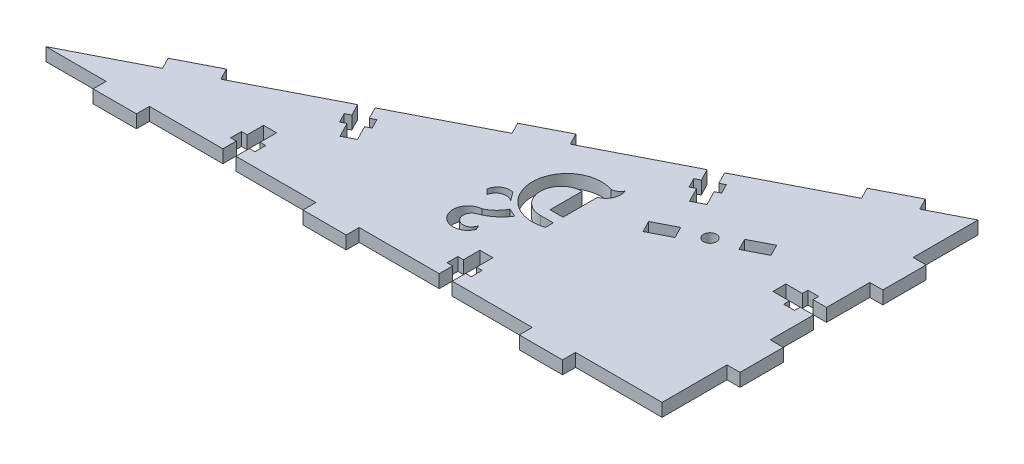
SolidWorks part; units mm, degrees
ref_plane "Front Plane" through (0, 0, 0) normal (0, 0, 1) x (1, 0, 0)
ref_plane "Top Plane" through (0, 0, 0) normal (0, 1, 0) x (1, 0, 0)
ref_plane "Right Plane" through (0, 0, 0) normal (1, 0, 0) x (0, 0, -1)
sketch "Sketch1" plane through (0, 0, 0) normal (0, 1, 0) x (1, 0, 0)
  line L0 (0, 73) -> (-8.8985, 68.4375)
  line L1 (0, 0) -> (-20, 0)
  line L2 (0, 0) -> (0, 15)
  line L5 (-124.5792, 9.125) -> (-125.948, 11.7946)
  line L6 (-125.948, 11.7946) -> (-117.0495, 16.3571)
  line L7 (-117.0495, 16.3571) -> (-115.6807, 13.6875)
  line L8 (-8.8985, 68.4375) -> (-10.2673, 71.1071)
  line L9 (-10.2673, 71.1071) -> (-19.1658, 66.5446)
  line L10 (-19.1658, 66.5446) -> (-17.797, 63.875)
  line L11 (-124.5792, 9.125) -> (-142.3763, 0)
  line L12 (-17.797, 63.875) -> (-38.7085, 53.1531)
  line L13 (-62.2896, 41.0625) -> (-63.6584, 43.7321)
  line L14 (-63.6584, 43.7321) -> (-72.5569, 39.1696)
  line L15 (-72.5569, 39.1696) -> (-71.1881, 36.5)
  line L16 (-71.1881, 36.5) -> (-92.0996, 25.7781)
  line L17 (-18.2, 44.675) -> (-23.0942, 42.1656)
  line L18 (-92.0996, 25.7781) -> (-90.6853, 23.0196)
  line L19 (-90.6853, 23.0196) -> (-89.5285, 23.6127)
  line L20 (-89.5285, 23.6127) -> (-88.3878, 21.3881)
  line L21 (-88.3878, 21.3881) -> (-89.5446, 20.795)
  line L22 (-89.5446, 20.795) -> (-87.8109, 17.4135)
  line L23 (-87.8109, 17.4135) -> (-90.4804, 16.0448)
  line L24 (-90.4804, 16.0448) -> (-92.2142, 19.4262)
  line L25 (-92.2142, 19.4262) -> (-93.371, 18.8331)
  line L26 (-93.371, 18.8331) -> (-94.5116, 21.0577)
  line L27 (-94.5116, 21.0577) -> (-93.3548, 21.6508)
  line L28 (-93.3548, 21.6508) -> (-94.7692, 24.4094)
  line L29 (-94.7692, 24.4094) -> (-115.6807, 13.6875)
  line L30 (-37.2942, 50.3946) -> (-38.7085, 53.1531)
  line L31 (-36.1374, 50.9877) -> (-37.2942, 50.3946)
  line L32 (-34.9967, 48.7631) -> (-36.1374, 50.9877)
  line L33 (-36.1535, 48.17) -> (-34.9967, 48.7631)
  line L34 (-34.4198, 44.7885) -> (-36.1535, 48.17)
  line L35 (-37.0894, 43.4198) -> (-34.4198, 44.7885)
  line L36 (-38.8231, 46.8012) -> (-37.0894, 43.4198)
  line L37 (-39.9799, 46.2081) -> (-38.8231, 46.8012)
  line L38 (-39.9637, 49.0258) -> (-41.1205, 48.4327)
  line L39 (-41.1205, 48.4327) -> (-39.9799, 46.2081)
  line L40 (-41.3781, 51.7844) -> (-39.9637, 49.0258)
  line L41 (-41.3781, 51.7844) -> (-62.2896, 41.0625)
  line L42 (-23.0942, 42.1656) -> (-21.7254, 39.4961)
  line L43 (-21.7254, 39.4961) -> (-16.8313, 42.0054)
  line L44 (-16.8313, 42.0054) -> (-18.2, 44.675)
  line L45 (-128.4763, 0) -> (-128.4763, -3)
  line L46 (-32.8584, 37.1592) -> (-31.4897, 34.4897)
  line L47 (-31.4897, 34.4897) -> (-36.3839, 31.9803)
  line L48 (-36.3839, 31.9803) -> (-37.7526, 34.6499)
  line L49 (-37.7526, 34.6499) -> (-32.8584, 37.1592)
  line L50 (-128.4763, -3) -> (-118.4763, -3)
  line L51 (-118.4763, -3) -> (-118.4763, 0)
  line L52 (-20, 0) -> (-20, -3)
  line L53 (-20, -3) -> (-30, -3)
  line L54 (-30, -3) -> (-30, 0)
  line L55 (-30, 0) -> (-48.5, 0)
  line L56 (-128.4763, 0) -> (-142.3763, 0)
  line L57 (-75, -3) -> (-75, 34.5456) construction
  line L58 (-70, 0) -> (-70, -3)
  line L59 (-70, -3) -> (-80, -3)
  line L60 (-80, -3) -> (-80, 0)
  line L61 (-80, 0) -> (-98.5, 0)
  line L62 (-48.5, 0) -> (-48.5, 3.1)
  line L63 (-48.5, 3.1) -> (-47.2, 3.1)
  line L64 (-47.2, 3.1) -> (-47.2, 5.6)
  line L65 (-47.2, 5.6) -> (-48.5, 5.6)
  line L66 (-48.5, 5.6) -> (-48.5, 9.4)
  line L67 (-48.5, 9.4) -> (-51.5, 9.4)
  line L68 (-51.5, 9.4) -> (-51.5, 5.6)
  line L69 (-51.5, 5.6) -> (-52.8, 5.6)
  line L70 (-52.8, 5.6) -> (-52.8, 3.1)
  line L71 (-52.8, 3.1) -> (-51.5, 3.1)
  line L72 (-51.5, 3.1) -> (-51.5, 0)
  line L73 (-51.5, 0) -> (-70, 0)
  line L74 (-101.5, 9.4) -> (-98.5, 9.4)
  line L75 (-98.5, 9.4) -> (-98.5, 5.6)
  line L76 (-101.5, 5.6) -> (-101.5, 9.4)
  line L77 (-102.8, 5.6) -> (-101.5, 5.6)
  line L78 (-98.5, 5.6) -> (-97.2, 5.6)
  line L79 (-97.2, 5.6) -> (-97.2, 3.1)
  line L80 (-102.8, 3.1) -> (-102.8, 5.6)
  line L81 (-101.5, 3.1) -> (-102.8, 3.1)
  line L82 (-97.2, 3.1) -> (-98.5, 3.1)
  line L83 (-98.5, 3.1) -> (-98.5, 0)
  line L84 (-101.5, 0) -> (-101.5, 3.1)
  line L85 (-101.5, 0) -> (-118.4763, 0)
  line L86 (0, 58) -> (3, 58)
  line L87 (3, 58) -> (3, 48)
  line L88 (3, 48) -> (0, 48)
  line L89 (0, 58) -> (0, 73)
  line L90 (0, 15) -> (3, 15)
  line L91 (3, 15) -> (3, 25)
  line L92 (3, 25) -> (0, 25)
  line L93 (0, 25) -> (0, 35)
  line L94 (-3.1, 35) -> (-3.1, 33.7)
  line L95 (0, 38) -> (-3.1, 38)
  line L96 (-3.1, 38) -> (-3.1, 39.3)
  line L97 (-3.1, 39.3) -> (-5.6, 39.3)
  line L98 (-5.6, 39.3) -> (-5.6, 38)
  line L99 (-5.6, 38) -> (-9.4, 38)
  line L100 (-9.4, 38) -> (-9.4, 35)
  line L101 (-9.4, 35) -> (-5.6, 35)
  line L102 (-5.6, 35) -> (-5.6, 33.7)
  line L103 (-5.6, 33.7) -> (-3.1, 33.7)
  line L104 (-3.1, 35) -> (0, 35)
  line L105 (0, 38) -> (0, 48)
  line L106 (-48.5, 33.565) -> (-48.5, 25.5985)
  line L107 (-51.4919, 32.9954) -> (-51.4919, 25.5985)
  line L108 (-51.4919, 23.3485) -> (-48.5, 23.3485)
  line L109 (-48.5, 25.5985) -> (-51.4919, 25.5985)
  line L110 (-48.5, 23.3485) -> (-48.5, 21.5485)
  line L111 (-62.9453, 22.4999) -> (-61.8148, 21.3694)
  line L112 (-59.3487, 24.8485) -> (-57.8753, 22.9027)
  line L113 (-56.2193, 21.108) -> (-54.281, 20.2519)
  line L114 (-56.5626, 14.2091) -> (-56.0751, 13.1104)
  circle A0 centre (-27.3555, 38.4246) radius 1.5
  arc A1 (-48.5, 36.7256) -> (-48.5, 21.5485) centre (-51.1227, 29.137) ccw
  arc A2 (-51.4919, 32.9954) -> (-51.4919, 23.3485) centre (-51.4919, 28.1719) ccw
  arc A3 (-48.5, 36.7256) -> (-46.55, 38.05) centre (-48.5946, 38.9626) ccw
  arc A4 (-46.55, 38.05) -> (-48.5, 33.565) centre (-49.7675, 36.7825) cw
  arc A5 (-59.3487, 24.8485) -> (-62.9453, 22.4999) centre (-60.0545, 22.0012) ccw
  arc A6 (-61.8148, 21.3694) -> (-57.8753, 22.9027) centre (-59.3487, 20.8607) cw
  arc A7 (-56.2193, 21.108) -> (-59.5719, 17.9225) centre (-62.6164, 24.4837) cw
  arc A8 (-54.281, 20.2519) -> (-59.2956, 16.2661) centre (-62.6656, 25.6533) cw
  arc A9 (-59.5719, 17.9225) -> (-56.0751, 13.1104) centre (-59.2956, 14.4468) ccw
  arc A10 (-59.2956, 16.2661) -> (-56.5626, 14.2091) centre (-58.4961, 14.4843) ccw
  point P1 (-124.5792, 9.125)
  point P9 (-62.2896, 41.0625)
  point P54 (-22.4098, 40.8308)
  point P58 (-20, 0)
  point P77 (-47.2, 36.5)
  point P95 (0, 58)
  point P99 (0, 15)
  point P121 (-48.5, 33.51)
  point P127 (-48.5, 24.8485)
  point P138 (-56.2193, 20.8607)
  point P147 (-58.87, 15.5551)
  point P148 (-59.7161, 17.4396)
  point P149 (-59.2956, 16.2661)
  point P150 (-56.2193, 12.6275)
  point P151 (-59.2956, 14.4468)
  point P152 (-56.5626, 14.2091)
  point P153 (0, 0)
  dimension "D21" = 3
  dimension "D1" = 73
  dimension "D2" = 160
  dimension "D3" = 20
  dimension "D4" = 10
  dimension "D5" = 3
  dimension "D6" = 10
  dimension "D7" = 50
  dimension "D8" = 23.5
  dimension "D9" = 3.1
  dimension "D10" = 1.3
  dimension "D11" = 2.5
  dimension "D12" = 3.8
  dimension "D13" = 3
  dimension "D14" = 23.5
  dimension "D15" = 23.5
  dimension "D16" = 19.2
  dimension "D17" = 18.2
  dimension "D18" = 5.5
  dimension "D19" = 3
  dimension "D20" = 10.9729
  dimension "D22" = 5.5
  dimension "D23" = 13.9
  dimension "D24" = 40
  dimension "D25" = 20
  dimension "D26" = 2.5
  dimension "D27" = 3
  dimension "D28" = 3.8
  dimension "D29" = 3.1
  dimension "D30" = 1.3
  dimension "D31" = 18.5
  dimension "D32" = 15
  dimension "D33" = 3.1
  dimension "D34" = 2.5
  dimension "D35" = 3.8
  dimension "D36" = 3
  dimension "D37" = 10
  dimension "D38" = 1.3
  dimension "D39" = 1.5
  dimension "D40" = 1.8
extrude "Boss-Extrude1" add sketch "Sketch1" along normal blind 3
